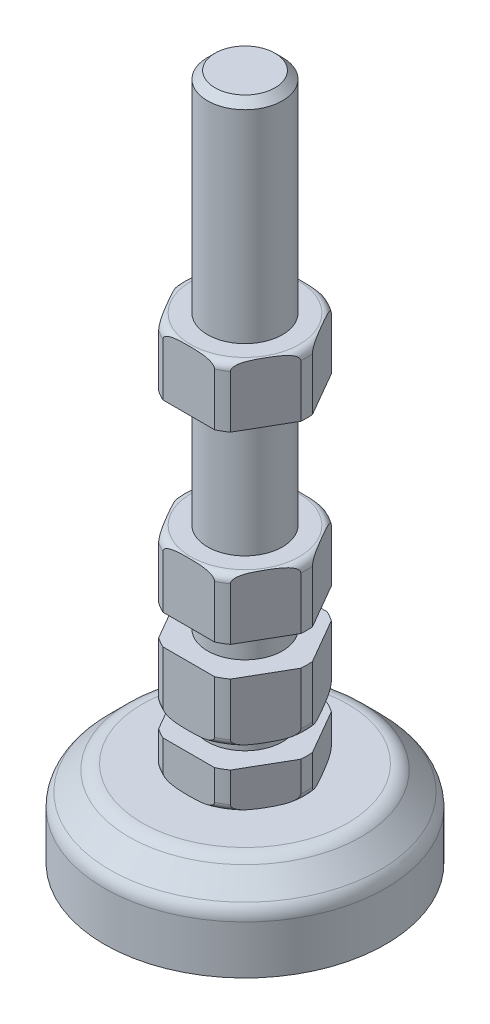
SolidWorks part; units mm, degrees
ref_plane "前基準面" through (0, 0, 0) normal (0, 0, 1) x (1, 0, 0)
ref_plane "上基準面" through (0, 0, 0) normal (0, 1, 0) x (1, 0, 0)
ref_plane "右基準面" through (0, 0, 0) normal (1, 0, 0) x (0, 0, -1)
sketch "草圖1" plane through (0, 0, 0) normal (0, 0, 1) x (1, 0, 0)
  line L0 (0, -13.8028) -> (0, 196.2431) construction
  line L1 (0, 0) -> (37.5, 0)
  line L2 (37.5, 0) -> (37.5, 12.9289)
  line L3 (36.0355, 16.4645) -> (30.9645, 21.5355)
  line L4 (27.4289, 23) -> (14.5, 23)
  line L5 (16.5, 25) -> (16.5, 33)
  line L6 (16.5, 33) -> (10, 33)
  line L7 (10, 33) -> (10, 38)
  line L8 (10, 62) -> (16.5, 62)
  line L9 (16.5, 62) -> (16.5, 76)
  line L10 (14.5, 78) -> (10, 78)
  line L11 (10, 78) -> (10, 111)
  line L12 (8, 183) -> (0, 183)
  line L13 (0, 183) -> (0, 0)
  line L14 (10, 181) -> (8, 183)
  line L15 (10, 54) -> (10, 62)
  line L16 (10, 54) -> (16.5, 54)
  line L17 (10, 127) -> (10, 181)
  line L18 (10, 38) -> (14.5, 38)
  line L19 (16.5, 54) -> (16.5, 40)
  line L20 (10, 127) -> (14.5, 127)
  line L22 (10, 111) -> (16.5, 111)
  line L23 (16.5, 125) -> (16.5, 111)
  arc A0 (16.5, 76) -> (14.5, 78) centre (14.5, 76) ccw
  arc A1 (16.5, 25) -> (14.5, 23) centre (14.5, 25) cw
  arc A2 (16.5, 40) -> (14.5, 38) centre (14.5, 40) cw
  arc A3 (16.5, 125) -> (14.5, 127) centre (14.5, 125) ccw
  arc A4 (30.9645, 21.5355) -> (27.4289, 23) centre (27.4289, 18) ccw
  arc A5 (37.5, 12.9289) -> (36.0355, 16.4645) centre (32.5, 12.9289) ccw
  point P13 (10, 183)
  point P18 (16.5, 62)
  point P27 (16.5, 78)
  point P40 (37.5, 15)
  dimension "D10" = 2
  dimension "D11" = 2
  dimension "D18" = 5
  dimension "D1" = 75
  dimension "D2" = 23
  dimension "D3" = 45
  dimension "D4" = 20
  dimension "D5" = 33
  dimension "D6" = 10
  dimension "D7" = 15
  dimension "D8" = 16
  dimension "D9" = 5
  dimension "D12" = 150
  dimension "D13" = 16
  dimension "D14" = 8
  dimension "D16" = 16
  dimension "D17" = 72
revolve "旋轉1" add sketch "草圖1" angle 360 about L0
sketch "草圖2" plane through (0, 127, 0) normal (0, 1, 0) x (1, 0, 0)
  line L0 (0, 0) -> (17.3205, 0) construction
  line L1 (17.3205, 0) -> (8.6603, 15)
  line L2 (8.6603, 15) -> (-8.6603, 15)
  line L3 (-8.6603, 15) -> (-17.3205, 0)
  line L4 (-17.3205, 0) -> (-8.6603, -15)
  line L5 (-8.6603, -15) -> (8.6603, -15)
  line L6 (8.6603, -15) -> (17.3205, 0)
  circle A0 centre (0, 0) radius 15 construction
  circle A1 centre (0, 0) radius 71.2813
  dimension "D1" = 30
extrude "除料-伸長3" cut sketch "草圖2" against normal up to surface (104 mm away) up to face at (0, 23, -14.5)
